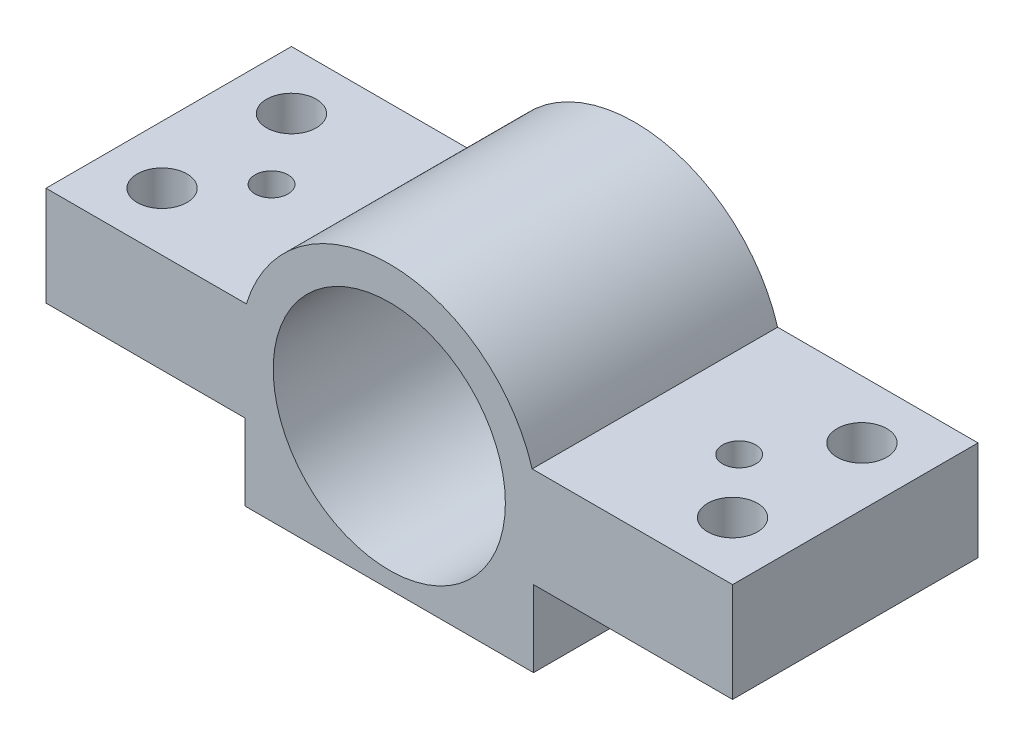
SolidWorks part; units mm, degrees
ref_plane "前视基准面" through (0, 0, 0) normal (0, 0, 1) x (1, 0, 0)
ref_plane "上视基准面" through (0, 0, 0) normal (0, 1, 0) x (1, 0, 0)
ref_plane "右视基准面" through (0, 0, 0) normal (1, 0, 0) x (0, 0, -1)
sketch "草图3" plane through (0, 0, 0) normal (0, 0, 1) x (1, 0, 0)
  line L0 (-43.5, 0) -> (43.5, 0)
  line L1 (55, 0) -> (-55, 0) construction
  line L3 (43.5, 0) -> (43.5, 23)
  line L4 (43.5, 23) -> (103.5, 23)
  line L5 (103.5, 23) -> (103.5, 53)
  line L6 (0, -55) -> (0, 55) construction
  line L7 (103.5, 53) -> (43.0813, 53)
  line L8 (-43.5, 0) -> (-43.5, 23)
  line L9 (-43.5, 23) -> (-103.5, 23)
  line L10 (-103.5, 23) -> (-103.5, 53)
  line L11 (-103.5, 53) -> (-43.0813, 53)
  circle A0 centre (0, 40) radius 35
  arc A2 (43.0813, 53) -> (-43.0813, 53) centre (0, 40) ccw
  point P6 (0, 0)
  dimension "D2" = 70
  dimension "D3" = 40
  dimension "D4" = 87
  dimension "D5" = 23
  dimension "D6" = 60
  dimension "D7" = 30
  dimension "D8" = 23
  dimension "D9" = 60
  dimension "D10" = 30
extrude "凸台-拉伸2" add sketch "草图3" along normal blind 74
sketch "草图4" plane through (0, 53, 0) normal (0, 1, 0) x (1, 0, 0)
  line L0 (-46.75, 0) -> (46.75, 0) construction
  line L1 (-103.5, -74) -> (-103.5, 0) construction
  line L3 (-43.0813, -74) -> (-103.5, -74) construction
  line L4 (103.5, -74) -> (103.5, 0) construction
  line L5 (103.5, -74) -> (43.0813, -74) construction
  circle A0 centre (86, -17.5) radius 7.5
  circle A1 centre (86, -56.5) radius 7.5
  circle A2 centre (70.5, -39) radius 5
  circle A3 centre (-86, -17.5) radius 7.5
  circle A4 centre (-86, -56.5) radius 7.5
  circle A5 centre (-70.5, -39) radius 5
  dimension "D1" = 15
  dimension "D2" = 10
  dimension "D6" = 17.5
  dimension "D7" = 33
  dimension "D8" = 35
  dimension "D9" = 17.5
  dimension "D10" = 17.5
  dimension "D11" = 17.5
  dimension "D12" = 17.5
  dimension "D13" = 33
  dimension "D14" = 35
  dimension "D3" = 17.5
  dimension "D4" = 17.5
  dimension "D5" = 17.5
extrude "切除-拉伸1" cut sketch "草图4" against normal through all
